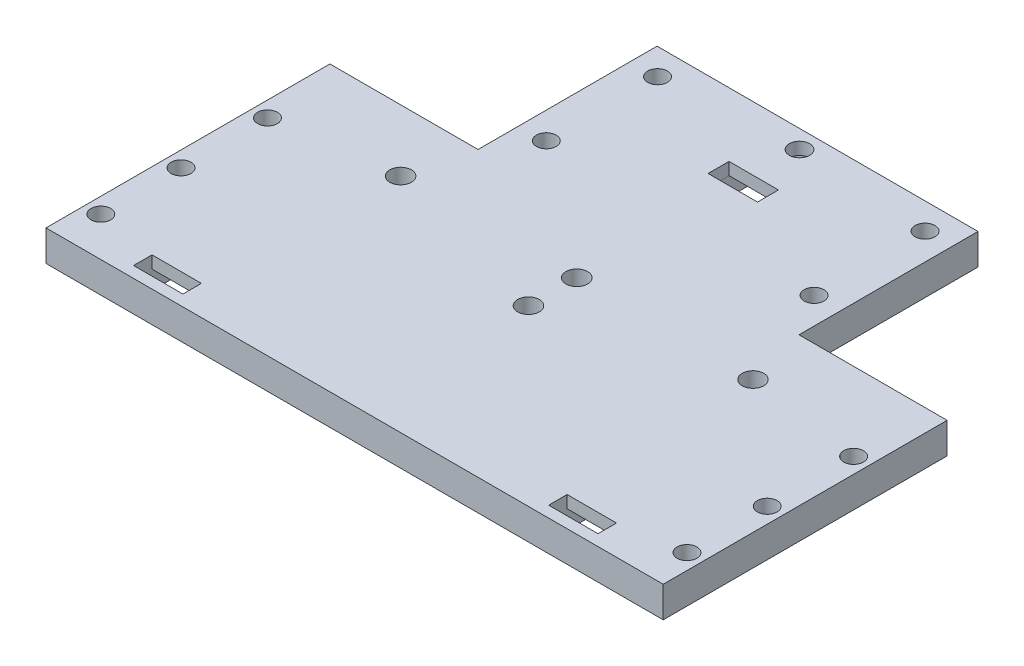
SolidWorks part; units mm, degrees
ref_plane "Alzado" through (0, 0, 0) normal (0, 0, 1) x (1, 0, 0)
ref_plane "Planta" through (0, 0, 0) normal (0, 1, 0) x (1, 0, 0)
ref_plane "Vista lateral" through (0, 0, 0) normal (1, 0, 0) x (0, 0, -1)
sketch "Croquis1" plane through (0, 0, 0) normal (0, 1, 0) x (1, 0, 0)
  line L0 (-50, 8.5) -> (-26, 8.5)
  line L1 (-50, 37.5) -> (50, 37.5)
  line L2 (-50, 37.5) -> (-50, -37.5)
  line L3 (-50, -37.5) -> (50, -37.5)
  line L4 (50, 37.5) -> (50, -37.5)
  line L5 (-50, 37.5) -> (50, -37.5) construction
  line L6 (-50, -37.5) -> (50, 37.5) construction
  line L7 (-26, 8.5) -> (-26, 37.5)
  line L8 (0, 0) -> (0, -18.4798) construction
  line L9 (26, 8.5) -> (26, 37.5)
  line L10 (50, 8.5) -> (26, 8.5)
  line L12 (-3.9962, 23.7649) -> (4.0149, 23.7649)
  line L13 (-3.9962, 23.7649) -> (-3.9962, 27.1565)
  line L14 (-3.9962, 27.1565) -> (4.0149, 27.1565)
  line L15 (4.0149, 23.7649) -> (4.0149, 27.1565)
  circle A0 centre (28.55, -1.5041) radius 1.75
  circle A1 centre (-28.55, -1.5041) radius 1.75
  circle A2 centre (0, -1.5041) radius 1.75
  circle A3 centre (0, -9.3293) radius 1.75
  circle A4 centre (47.4845, -4.1356) radius 1.5
  circle A5 centre (47.4845, -18.1356) radius 1.5
  circle A6 centre (47.4845, -31.1356) radius 1.5
  circle A7 centre (-47.4845, -18.1356) radius 1.5
  circle A8 centre (-47.4845, -4.1356) radius 1.5
  circle A9 centre (-47.4845, -31.1356) radius 1.5
  circle A10 centre (0.0445, 34.5351) radius 1.6426
  circle A11 centre (21.6914, 15.25) radius 1.5
  circle A12 centre (21.6704, 33.25) radius 1.5
  circle A13 centre (30.3296, 33.25) radius 1.5
  circle A14 centre (30.3086, 15.25) radius 1.5
  circle A15 centre (-21.6704, 33.25) radius 1.5
  circle A16 centre (-21.6914, 15.25) radius 1.5
  circle A17 centre (-39.7784, -48.0407) radius 1.645
  circle A18 centre (39.7784, -48.0407) radius 1.645
  point P0 (0, 0)
  dimension "D5" = 3.5
  dimension "D6" = 3.5
  dimension "D7" = 3.5
  dimension "D8" = 3.5
  dimension "D9" = 3.2852
  dimension "D10" = 3
  dimension "D11" = 3
  dimension "D12" = 3.29
  dimension "D1" = 75
  dimension "D2" = 100
  dimension "D3" = 29
  dimension "D4" = 24
extrude "Saliente-Extruir1" add sketch "Croquis1" along normal blind 5 contours L4 L10 L9 L1 L7 L0 L2 L3
hole_wizard "Refrentado para tornillo tapón con cabeza plana de clavija de M31" positions "Croquis3D4" profile "Croquis4" countersink size "M3" standard "Ansi Metric" end condition through all
sketch3d "Croquis3D4"
  line L0 (47.4845, 5, 4.1356) -> (47.4845, 0, 4.1356) construction
  line L1 (47.4845, 5, 18.1356) -> (47.4845, 0, 18.1356) construction
  line L2 (47.4845, 5, 31.1356) -> (47.4845, 0, 31.1356) construction
  line L3 (-47.4845, 5, 31.1356) -> (-47.4845, 0, 31.1356) construction
  line L4 (-47.4845, 5, 18.1356) -> (-47.4845, 0, 18.1356) construction
  line L5 (-47.4845, 5, 4.1356) -> (-47.4845, 0, 4.1356) construction
  line L6 (-21.6914, 5, -15.25) -> (-21.6914, 0, -15.25) construction
  line L7 (21.6914, 5, -15.25) -> (21.6914, 0, -15.25) construction
  line L8 (21.6704, 5, -33.25) -> (21.6704, 0, -33.25) construction
  line L9 (0.0445, 5, -34.5351) -> (0.0445, 0, -34.5351) construction
  line L10 (-21.6704, 5, -33.25) -> (-21.6704, 0, -33.25) construction
  point P0 (47.4845, 0, 4.1356)
  point P4 (47.4845, 0, 18.1356)
  point P8 (47.4845, 0, 31.1356)
  point P12 (-47.4845, 0, 31.1356)
  point P16 (-47.4845, 0, 18.1356)
  point P20 (-47.4845, 0, 4.1356)
  point P24 (-21.6914, 0, -15.25)
  point P28 (21.6914, 0, -15.25)
  point P32 (21.6704, 0, -33.25)
  point P36 (0.0445, 0, -34.5351)
  point P40 (-21.6704, 0, -33.25)
sketch "Croquis4" plane through (47.4845, 0, 4.1356) normal (1, 0, 0) x (0, 0, -1)
  line L0 (0, 0) -> (0, 5)
  line L1 (0, 5) -> (1.6, 5)
  line L2 (1.6, 5) -> (1.6, 0.76)
  line L3 (1.6, 0.76) -> (2.36, 0)
  line L5 (2.36, 0) -> (0, 0)
  line L6 (-1.6, 0.76) -> (-2.36, 0) construction
  line L11 (0, -6.35) -> (0, 107.95) construction
  dimension "Diámetro de taladro hasta el siguiente" = 3.2
  dimension "Profundidad de taladro hasta el siguiente" = 5
  dimension "Diámetro de avellanado cercano" = 4.72
  dimension "Ángulo de avellanado cercano" = 90
hole_wizard "Refrentado para tornillo tapón con cabeza plana de clavija de M32" positions "Croquis3D6" profile "Croquis6" countersink size "M3" standard "Ansi Metric" end condition through all
sketch3d "Croquis3D6"
  line L0 (28.55, 5, 1.5041) -> (28.55, 0, 1.5041) construction
  line L1 (0, 5, 9.3293) -> (0, 0, 9.3293) construction
  line L2 (0, 5, 1.5041) -> (0, 0, 1.5041) construction
  line L3 (-28.55, 5, 1.5041) -> (-28.55, 0, 1.5041) construction
  point P0 (28.55, 0, 1.5041)
  point P4 (0, 0, 9.3293)
  point P8 (0, 0, 1.5041)
  point P12 (-28.55, 0, 1.5041)
sketch "Croquis6" plane through (28.55, 0, 1.5041) normal (1, 0, 0) x (0, 0, -1)
  line L0 (0, 0) -> (0, 5)
  line L1 (0, 5) -> (1.6, 5)
  line L2 (1.6, 5) -> (1.6, 1.76)
  line L3 (1.6, 1.76) -> (3.36, 0)
  line L5 (3.36, 0) -> (0, 0)
  line L6 (-1.6, 1.76) -> (-3.36, 0) construction
  line L11 (0, -6.35) -> (0, 107.95) construction
  dimension "Diámetro de taladro hasta el siguiente" = 3.2
  dimension "Profundidad de taladro hasta el siguiente" = 5
  dimension "Diámetro de avellanado cercano" = 6.72
  dimension "Ángulo de avellanado cercano" = 90
sketch "Croquis7" plane through (0, 0, 0) normal (0, -1, 0) x (1, 0, 0)
  line L0 (-26, -37.5) -> (26, -37.5) construction
  line L1 (-37.6269, 35.6901) -> (-29.6269, 35.6901)
  line L2 (-4, -23.65) -> (4, -23.65)
  line L3 (-4, -23.65) -> (-4, -37.15)
  line L4 (-4, -37.15) -> (4, -37.15)
  line L5 (4, -23.65) -> (4, -37.15)
  line L6 (-4, -23.65) -> (4, -37.15) construction
  line L7 (-4, -37.15) -> (4, -23.65) construction
  line L8 (0, -37.5) -> (0, -42.8245) construction
  line L9 (-37.6269, 35.6901) -> (-37.6269, 22.1901)
  line L10 (-37.6269, 22.1901) -> (-29.6269, 22.1901)
  line L11 (-29.6269, 35.6901) -> (-29.6269, 22.1901)
  line L12 (-37.6269, 35.6901) -> (-29.6269, 22.1901) construction
  line L13 (-37.6269, 22.1901) -> (-29.6269, 35.6901) construction
  line L14 (0, 37.5) -> (0, 18.6334) construction
  line L15 (-50, 37.5) -> (50, 37.5) construction
  line L16 (37.6269, 22.1901) -> (29.6269, 35.6901) construction
  line L17 (37.6269, 35.6901) -> (29.6269, 22.1901) construction
  line L18 (29.6269, 35.6901) -> (29.6269, 22.1901)
  line L19 (37.6269, 22.1901) -> (29.6269, 22.1901)
  line L20 (37.6269, 35.6901) -> (37.6269, 22.1901)
  line L21 (37.6269, 35.6901) -> (29.6269, 35.6901)
  point P4 (0, -30.4)
  point P9 (-33.6269, 28.9401)
  point P25 (33.6269, 28.9401)
  dimension "D1" = 8
  dimension "D2" = 13.5
  dimension "D3" = 0.35
  dimension "D4" = 8
  dimension "D5" = 13.5
extrude "Cortar-Extruir1" cut sketch "Croquis7" against normal blind 3
sketch "Croquis8" plane through (0, 3, 0) normal (0, -1, 0) x (1, 0, 0)
  line L0 (-29.6269, 22.1901) -> (-29.6269, 35.6901) construction
  line L1 (-37.6269, 35.6901) -> (-29.6269, 35.6901)
  line L2 (-37.6269, 35.6901) -> (-37.6269, 32.6965)
  line L3 (-37.6269, 32.6965) -> (-29.6269, 32.6965)
  line L4 (-29.6269, 35.6901) -> (-29.6269, 32.6965)
  line L5 (37.6269, 22.1901) -> (37.6269, 35.6901) construction
  line L6 (29.6269, 35.6901) -> (37.6269, 35.6901)
  line L7 (29.6269, 35.6901) -> (29.6269, 32.6965)
  line L8 (29.6269, 32.6965) -> (37.6269, 32.6965)
  line L9 (37.6269, 35.6901) -> (37.6269, 32.6965)
extrude "Cortar-Extruir2" cut sketch "Croquis8" against normal blind 10
